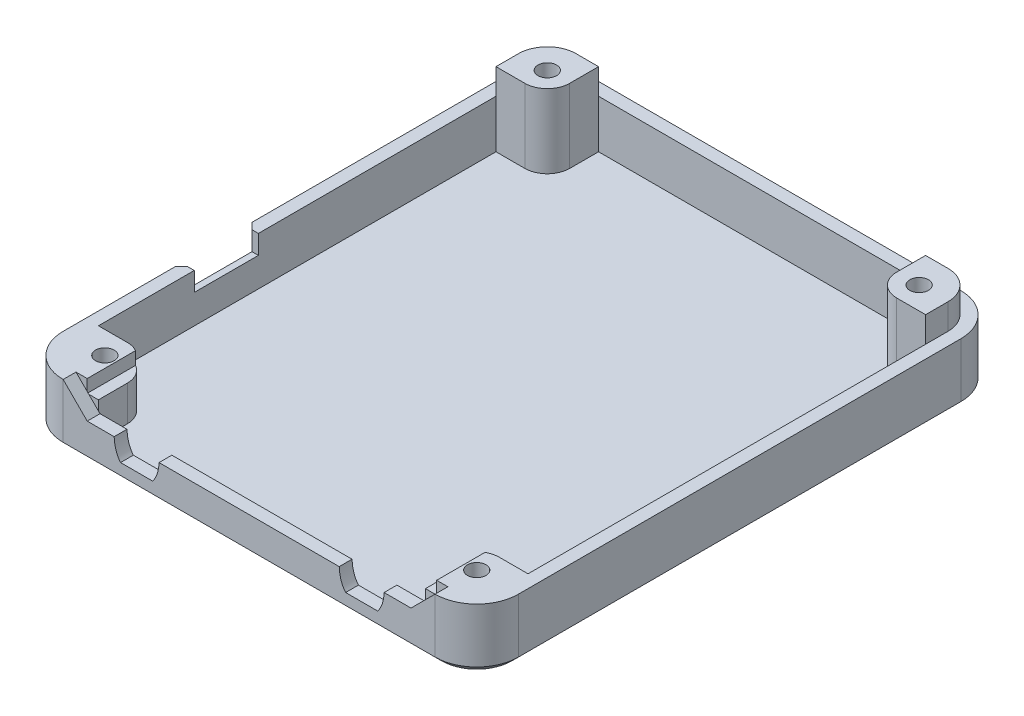
SolidWorks part; units mm, degrees
ref_plane "Front Plane" through (0, 0, 0) normal (0, 0, 1) x (1, 0, 0)
ref_plane "Top Plane" through (0, 0, 0) normal (0, 1, 0) x (1, 0, 0)
ref_plane "Right Plane" through (0, 0, 0) normal (1, 0, 0) x (0, 0, -1)
sketch "Sketch1" plane through (0, 0, 0) normal (0, 1, 0) x (1, 0, 0)
  line L0 (-33.8462, -25.5532) -> (31.1538, -25.5532)
  line L1 (-33.8462, 38.4468) -> (31.1538, 38.4468)
  line L2 (-33.8462, 38.4468) -> (-33.8462, 8.4468)
  line L3 (-33.8462, 8.4468) -> (31.1538, 8.4468)
  line L4 (31.1538, 38.4468) -> (31.1538, 8.4468)
  line L5 (-30.3462, 34.9468) -> (27.6538, 34.9468)
  line L6 (-30.3462, 34.9468) -> (-30.3462, 11.9468)
  line L7 (-30.3462, 11.9468) -> (27.6538, 11.9468)
  line L8 (27.6538, 34.9468) -> (27.6538, 11.9468)
  line L9 (-30.3462, 0.9468) -> (27.6538, 0.9468)
  line L10 (-30.3462, 0.9468) -> (-30.3462, -22.0532)
  line L11 (-33.8462, 4.4468) -> (31.1538, 4.4468)
  line L12 (-33.8462, 4.4468) -> (-33.8462, -25.5532)
  line L13 (-30.3462, -22.0532) -> (27.6538, -22.0532)
  line L14 (31.1538, 4.4468) -> (31.1538, -25.5532)
  line L15 (27.6538, 0.9468) -> (27.6538, -22.0532)
  line L16 (-37.9161, 25.3468) -> (-35.3276, 25.3468)
  line L17 (7.5538, 7.5472) -> (7.5538, 6.2645)
  line L18 (20.1538, 7.5472) -> (20.1538, 6.2645)
  dimension "D1" = 65
  dimension "D2" = 30
  dimension "D3" = 58
  dimension "D4" = 23
  dimension "D5" = 3.5
  dimension "D6" = 3.5
  dimension "D7" = 65
  dimension "D8" = 30
  dimension "D9" = 58
  dimension "D10" = 23
  dimension "D11" = 3.5
  dimension "D12" = 3.5
  dimension "D13" = 4
  dimension "D14" = 16.9
  dimension "D15" = 41.4
  dimension "D16" = 54
sketch "Sketch2" plane through (0, 0, 0) normal (0, 1, 0) x (1, 0, 0)
  line L0 (-33.8462, 38.4468) -> (-33.8462, 8.4468) construction
  line L1 (-30.3462, 39.4468) -> (27.6538, 39.4468)
  line L2 (-34.8462, 34.9468) -> (-34.8462, -34.0532)
  line L3 (-30.3462, -38.5532) -> (27.6538, -38.5532)
  line L4 (32.1538, 34.9468) -> (32.1538, -34.0532)
  line L5 (-33.8462, 38.4468) -> (31.1538, 38.4468) construction
  line L6 (31.1538, 38.4468) -> (31.1538, 8.4468) construction
  line L7 (-30.3462, 41.4468) -> (27.6538, 41.4468)
  line L8 (34.1538, 34.9468) -> (34.1538, -34.0532)
  line L9 (-30.3462, -40.5532) -> (27.6538, -40.5532)
  line L10 (-36.8462, 34.9468) -> (-36.8462, -34.0532)
  line L11 (-34.8462, 39.4468) -> (32.1538, 39.4468) construction
  line L12 (-34.8462, 39.4468) -> (-34.8462, -38.5532) construction
  line L13 (-36.8462, 41.4468) -> (-36.8462, -40.5532) construction
  line L14 (-36.8462, 41.4468) -> (34.1538, 41.4468) construction
  line L15 (32.1538, 39.4468) -> (32.1538, -38.5532) construction
  line L16 (34.1538, 41.4468) -> (34.1538, -40.5532) construction
  line L17 (-36.8462, -40.5532) -> (34.1538, -40.5532) construction
  line L18 (-34.8462, -38.5532) -> (32.1538, -38.5532) construction
  arc A0 (-30.3462, 39.4468) -> (-34.8462, 34.9468) centre (-30.3462, 34.9468) ccw
  arc A1 (-36.8462, 34.9468) -> (-30.3462, 41.4468) centre (-30.3462, 34.9468) cw
  arc A2 (32.1538, 34.9468) -> (27.6538, 39.4468) centre (27.6538, 34.9468) ccw
  arc A3 (34.1538, 34.9468) -> (27.6538, 41.4468) centre (27.6538, 34.9468) ccw
  arc A4 (27.6538, -40.5532) -> (34.1538, -34.0532) centre (27.6538, -34.0532) ccw
  arc A5 (-36.8462, -34.0532) -> (-30.3462, -40.5532) centre (-30.3462, -34.0532) ccw
  arc A6 (27.6538, -38.5532) -> (32.1538, -34.0532) centre (27.6538, -34.0532) ccw
  arc A7 (-30.3462, -38.5532) -> (-34.8462, -34.0532) centre (-30.3462, -34.0532) cw
  dimension "D6" = 4.5
  dimension "D7" = 6.5
  dimension "D8" = 4.5
  dimension "D9" = 6.5
  dimension "D10" = 6.5
  dimension "D11" = 4.5
  dimension "D1" = 1
  dimension "D2" = 1
  dimension "D3" = 1
  dimension "D4" = 78
  dimension "D5" = 2
extrude "Boss-Extrude1" add sketch "Sketch2" along normal blind 9.5
sketch "Sketch3" plane through (0, 0, 0) normal (0, 1, 0) x (1, 0, 0)
  line L0 (-30.3462, -38.5532) -> (27.6538, -38.5532)
  line L1 (-30.3462, 39.4468) -> (27.6538, 39.4468)
  line L2 (-34.8462, 34.9468) -> (-34.8462, -34.0532)
  line L4 (32.1538, 34.9468) -> (32.1538, -34.0532)
  arc A0 (27.6538, -38.5532) -> (32.1538, -34.0532) centre (27.6538, -34.0532) ccw
  arc A1 (-34.8462, -34.0532) -> (-30.3462, -38.5532) centre (-30.3462, -34.0532) ccw
  arc A2 (32.1538, 34.9468) -> (27.6538, 39.4468) centre (27.6538, 34.9468) ccw
  arc A3 (-30.3462, 39.4468) -> (-34.8462, 34.9468) centre (-30.3462, 34.9468) ccw
  point P15 (-34.8462, 39.4468)
  dimension "D1" = 4.5
extrude "Boss-Extrude2" add sketch "Sketch3" along normal blind 2
sketch "Sketch6" plane through (0, 2, 0) normal (0, 1, 0) x (1, 0, 0)
  line L3 (-34.8462, 34.9468) -> (-34.8462, -34.0532) construction
  line L5 (-26.8462, 34.9468) -> (-26.8462, 39.4468)
  line L6 (27.6538, 39.4468) -> (-30.3462, 39.4468) construction
  line L7 (-26.8462, 39.4468) -> (-30.3462, 39.4468)
  line L8 (-30.3462, 31.4468) -> (-34.8462, 31.4468)
  line L9 (-34.8462, 31.4468) -> (-34.8462, 34.9468)
  line L10 (24.1538, 34.9468) -> (24.1538, 39.4468)
  line L11 (24.1538, 39.4468) -> (27.6538, 39.4468)
  line L12 (27.6538, 31.4468) -> (32.1538, 31.4468)
  line L13 (32.1538, -34.0532) -> (32.1538, 34.9468) construction
  line L14 (32.1538, 31.4468) -> (32.1538, 34.9468)
  arc A0 (-30.3462, 31.4468) -> (-26.8462, 34.9468) centre (-30.3462, 34.9468) ccw
  arc A1 (24.1538, 34.9468) -> (27.6538, 31.4468) centre (27.6538, 34.9468) ccw
  arc A4 (-30.3462, 39.4468) -> (-34.8462, 34.9468) centre (-30.3462, 34.9468) ccw
  arc A5 (32.1538, 34.9468) -> (27.6538, 39.4468) centre (27.6538, 34.9468) ccw
  dimension "D1" = 4.5
  dimension "D2" = 4.5
extrude "Boss-Extrude4" add sketch "Sketch6" along normal blind 11.5
sketch "Sketch7" plane through (0, 0, 40.5532) normal (0, 0, 1) x (1, 0, 0)
  line L0 (27.6538, 9.5) -> (-30.3462, 9.5)
  line L1 (-21.3969, 2.7488) -> (-16.3969, 2.7488)
  line L2 (16.2046, 5.7488) -> (16.2046, 2.7488) construction
  line L3 (-18.8969, 5.7488) -> (-18.8969, 2.7488) construction
  line L4 (-1.3462, 9.5) -> (-1.3462, 13.2512) construction
  line L5 (-30.3462, 9.5) -> (27.6538, 9.5) construction
  line L6 (13.7046, 2.7488) -> (18.7046, 2.7488)
  line L20 (27.6538, 9.5) -> (23.9027, 5.7488)
  line L21 (23.9027, 5.7488) -> (19.7046, 5.7488)
  line L22 (12.7046, 5.7488) -> (-15.3969, 5.7488)
  line L23 (-26.595, 5.7488) -> (-22.3969, 5.7488)
  line L24 (-30.3462, 9.5) -> (-26.595, 5.7488)
  spline S0 degree 2 poles (-15.3969, 5.7488) (-15.4754, 3.8677) (-16.3969, 2.7488) knots 0 0 0 0.447397 0.447397 0.447397
  spline S1 degree 2 poles (-22.3969, 5.7488) (-22.3185, 3.8677) (-21.3969, 2.7488) knots 0 0 0 0.447397 0.447397 0.447397
  spline S2 degree 2 poles (12.7046, 5.7488) (12.7831, 3.8677) (13.7046, 2.7488) knots 0 0 0 0.447397 0.447397 0.447397
  spline S3 degree 2 poles (19.7046, 5.7488) (19.6262, 3.8677) (18.7046, 2.7488) knots 0 0 0 0.447397 0.447397 0.447397
  dimension "D1" = 7
  dimension "D2" = 7
sketch "Sketch8" plane through (0, 2, 0) normal (0, 1, 0) x (1, 0, 0)
  line L9 (32.1538, -30.5532) -> (32.1538, -34.0532)
  line L10 (27.6538, -30.5532) -> (32.1538, -30.5532)
  line L11 (24.1538, -38.5532) -> (27.6538, -38.5532)
  line L12 (24.1538, -34.0532) -> (24.1538, -38.5532)
  line L13 (-34.8462, -30.5532) -> (-34.8462, -34.0532)
  line L14 (-30.3462, -30.5532) -> (-34.8462, -30.5532)
  line L15 (-26.8462, -38.5532) -> (-30.3462, -38.5532)
  line L16 (-26.8462, -34.0532) -> (-26.8462, -38.5532)
  arc A4 (32.1538, -34.0532) -> (27.6538, -38.5532) centre (27.6538, -34.0532) cw
  arc A5 (-30.3462, -38.5532) -> (-34.8462, -34.0532) centre (-30.3462, -34.0532) cw
  arc A6 (24.1538, -34.0532) -> (27.6538, -30.5532) centre (27.6538, -34.0532) cw
  arc A7 (-30.3462, -30.5532) -> (-26.8462, -34.0532) centre (-30.3462, -34.0532) cw
extrude "Boss-Extrude6" add sketch "Sketch8" along normal up to vertex
extrude "Cut-Extrude1" cut sketch "Sketch7" against normal up to vertex (2 mm away)
sketch "Sketch9" plane through (-36.8462, 0, 0) normal (-1, 0, 0) x (0, 0, 1)
  line L1 (15.6062, 9.5338) -> (5.6062, 9.5338)
  line L2 (15.6062, 9.5338) -> (15.6062, 6.5338)
  line L3 (15.6062, 6.5338) -> (5.6062, 6.5338)
  line L4 (5.6062, 9.5338) -> (5.6062, 6.5338)
  line L5 (15.6062, 9.5338) -> (5.6062, 6.5338) construction
  line L6 (15.6062, 6.5338) -> (5.6062, 9.5338) construction
  point P0 (10.6062, 8.0338)
  dimension "D1" = 10
  dimension "D2" = 3
extrude "Cut-Extrude2" cut sketch "Sketch9" against normal up to next
chamfer "Chamfer1" distance 1 angle 45 3 edges at (-36.8462, 8.0169, 5.6062) (-36.8462, 8.0169, 15.6062) (-36.8462, 6.5338, 10.6062)
chamfer "Chamfer2" distance 1 angle 45 8 edges at (-36.8462, 0, -0.4468) (-34.9423, 0, 38.6493) (-34.9423, 0, -39.543) (-1.3462, 0, 40.5532) (-1.3462, 0, -41.4468) (32.25, 0, 38.6493) (32.25, 0, -39.543) (34.1538, 0, -0.4468)
hole_wizard "CBORE for M2.5 Pan Head Machine Screw1" positions "Sketch11" profile "Sketch10" counterbore size "M2.5" standard "ANSI Metric" end condition through all
sketch "Sketch11" plane through (0, 0, 0) normal (0, -1, 0) x (-1, 0, 0)
  point P0 (-27.6538, 34.9468)
sketch "Sketch10" plane through (27.6538, 0, -34.9468) normal (1, 0, 0) x (0, 0, -1)
  line L0 (0, 0) -> (0, 13.5)
  line L1 (0, 13.5) -> (1.45, 13.5)
  line L3 (1.45, 13.5) -> (1.45, 2.1)
  line L4 (1.45, 2.1) -> (3, 2.1)
  line L5 (3, 2.1) -> (3, 0)
  line L7 (3, 0) -> (0, 0)
  line L11 (0, -6.35) -> (0, 107.95) construction
  dimension "Thru Hole Dia." = 2.9
  dimension "Thru Hole Depth" = 13.5
  dimension "C'Bore Dia." = 6
  dimension "C'Bore Depth" = 2.1
hole_wizard "CBORE for M2.5 Pan Head Machine Screw2" positions "Sketch13" profile "Sketch12" counterbore size "M2.5" standard "ANSI Metric" end condition through all
sketch "Sketch13" plane through (0, 0, 0) normal (0, -1, 0) x (-1, 0, 0)
  point P0 (30.3462, 34.9468)
sketch "Sketch12" plane through (-30.3462, 0, -34.9468) normal (1, 0, 0) x (0, 0, -1)
  line L0 (0, 0) -> (0, 13.5)
  line L1 (0, 13.5) -> (1.45, 13.5)
  line L3 (1.45, 13.5) -> (1.45, 2.1)
  line L4 (1.45, 2.1) -> (3, 2.1)
  line L5 (3, 2.1) -> (3, 0)
  line L7 (3, 0) -> (0, 0)
  line L11 (0, -6.35) -> (0, 107.95) construction
  dimension "Thru Hole Dia." = 2.9
  dimension "Thru Hole Depth" = 13.5
  dimension "C'Bore Dia." = 6
  dimension "C'Bore Depth" = 2.1
hole_wizard "CBORE for M2.5 Pan Head Machine Screw3" positions "Sketch15" profile "Sketch14" counterbore size "M2.5" standard "ANSI Metric" end condition through all
sketch "Sketch15" plane through (0, 0, 0) normal (0, -1, 0) x (-1, 0, 0)
  point P0 (-27.6538, -34.0532)
sketch "Sketch14" plane through (27.6538, 0, 34.0532) normal (1, 0, 0) x (0, 0, -1)
  line L0 (0, 0) -> (0, 13.5)
  line L1 (0, 13.5) -> (1.45, 13.5)
  line L3 (1.45, 13.5) -> (1.45, 2.1)
  line L4 (1.45, 2.1) -> (3, 2.1)
  line L5 (3, 2.1) -> (3, 0)
  line L7 (3, 0) -> (0, 0)
  line L11 (0, -6.35) -> (0, 107.95) construction
  dimension "Thru Hole Dia." = 2.9
  dimension "Thru Hole Depth" = 13.5
  dimension "C'Bore Dia." = 6
  dimension "C'Bore Depth" = 2.1
hole_wizard "CBORE for M2.5 Pan Head Machine Screw4" positions "Sketch17" profile "Sketch16" counterbore size "M2.5" standard "ANSI Metric" end condition through all
sketch "Sketch17" plane through (0, 0, 0) normal (0, -1, 0) x (-1, 0, 0)
  point P0 (30.3462, -34.0532)
sketch "Sketch16" plane through (-30.3462, 0, 34.0532) normal (1, 0, 0) x (0, 0, -1)
  line L0 (0, 0) -> (0, 13.5)
  line L1 (0, 13.5) -> (1.45, 13.5)
  line L3 (1.45, 13.5) -> (1.45, 2.1)
  line L4 (1.45, 2.1) -> (3, 2.1)
  line L5 (3, 2.1) -> (3, 0)
  line L7 (3, 0) -> (0, 0)
  line L11 (0, -6.35) -> (0, 107.95) construction
  dimension "Thru Hole Dia." = 2.9
  dimension "Thru Hole Depth" = 13.5
  dimension "C'Bore Dia." = 6
  dimension "C'Bore Depth" = 2.1
sketch "Sketch18" plane through (0, 9.5, 0) normal (0, 1, 0) x (1, 0, 0)
  line L0 (-26.8462, -38.5532) -> (-30.3462, -38.5532) construction
  line L1 (-28.5962, -38.5532) -> (25.9038, -38.5532)
  line L2 (-28.5962, -38.5532) -> (-28.5962, -31.0221)
  line L3 (-28.5962, -31.0221) -> (25.9038, -31.0221)
  line L4 (25.9038, -38.5532) -> (25.9038, -31.0221)
  arc A0 (27.6538, -30.5532) -> (24.1538, -34.0532) centre (27.6538, -34.0532) ccw construction
extrude "Cut-Extrude3" cut sketch "Sketch18" against normal blind 2
